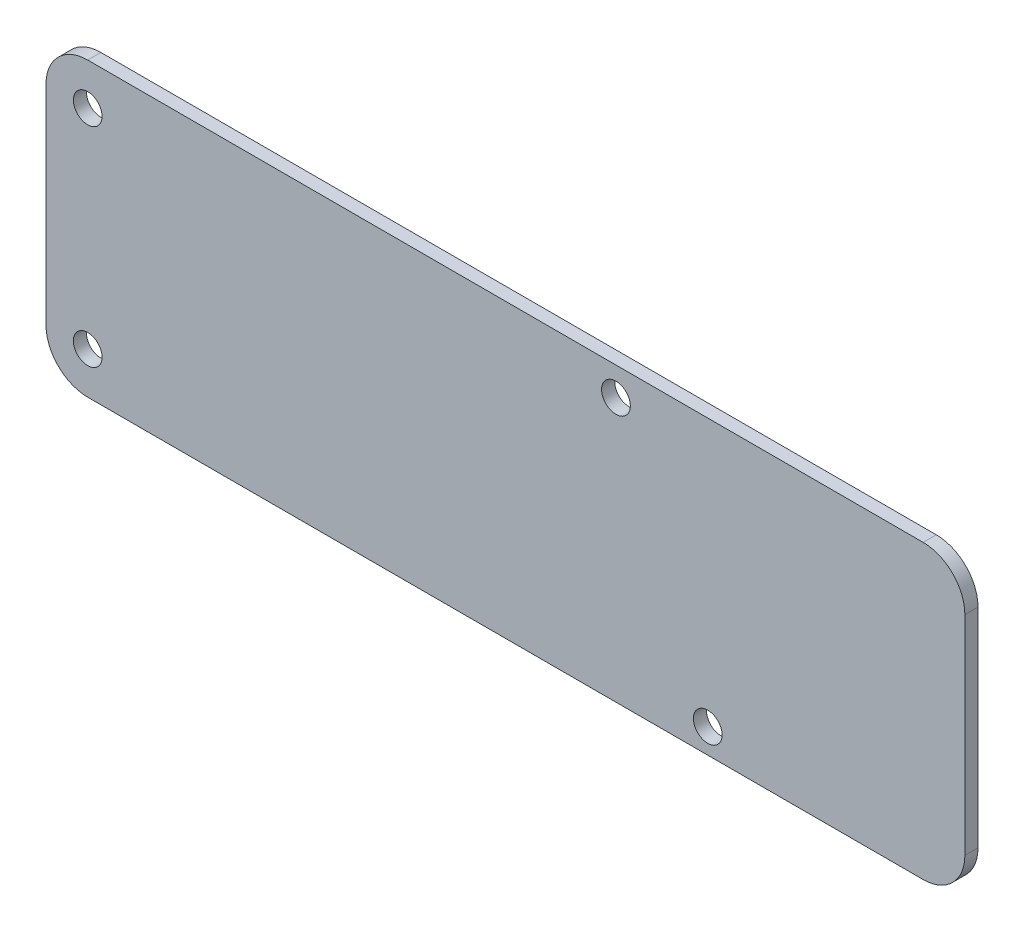
SolidWorks part; units mm, degrees
ref_plane "Front Plane" through (0, 0, 0) normal (0, 0, 1) x (1, 0, 0)
ref_plane "Top Plane" through (0, 0, 0) normal (0, 1, 0) x (1, 0, 0)
ref_plane "Right Plane" through (0, 0, 0) normal (1, 0, 0) x (0, 0, -1)
sketch "Sketch1" plane through (0, 0, 0) normal (0, 0, 1) x (1, 0, 0)
  line L1 (0, 5.08) -> (101.74, 5.08)
  line L2 (-5.08, 0) -> (-5.08, -25.4)
  line L3 (0, -30.48) -> (101.74, -30.48)
  line L4 (106.82, 0) -> (106.82, -25.4)
  circle A0 centre (0, 0) radius 1.75
  circle A1 centre (0, -25.4) radius 1.75
  circle A2 centre (64.33, 1.63) radius 1.75
  circle A3 centre (75.51, -27.48) radius 1.75
  arc A4 (-5.08, -25.4) -> (0, -30.48) centre (0, -25.4) ccw
  arc A5 (101.74, -30.48) -> (106.82, -25.4) centre (101.74, -25.4) ccw
  arc A6 (101.74, 5.08) -> (106.82, 0) centre (101.74, 0) cw
  arc A7 (0, 5.08) -> (-5.08, 0) centre (0, 0) ccw
  point P0 (0, 0)
  point P1 (64.33, 1.63)
  point P3 (75.51, -27.48)
  point P4 (0, -25.4)
  point P19 (-5.08, -30.48)
  point P22 (106.82, -30.48)
  dimension "D6" = 3.5
  dimension "D11" = 5.08
  dimension "D1" = 64.33
  dimension "D2" = 75.51
  dimension "D3" = 1.63
  dimension "D4" = 25.4
  dimension "D5" = 27.48
  dimension "D7" = 35.56
  dimension "D8" = 5.08
  dimension "D9" = 5.08
  dimension "D10" = 111.9
extrude "Boss-Extrude1" add sketch "Sketch1" along normal blind 1.6
